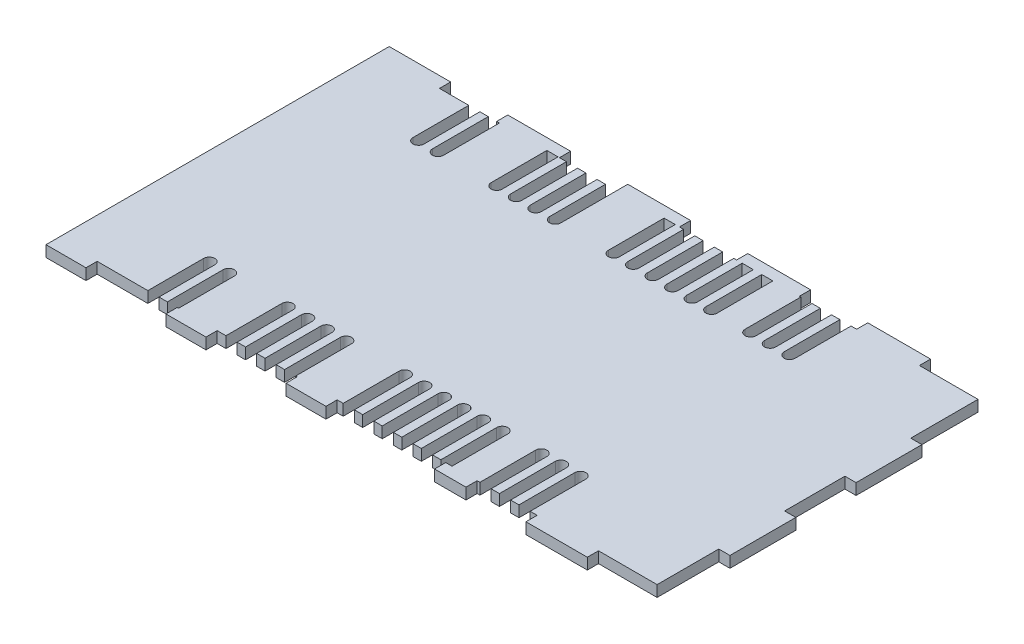
SolidWorks part; units mm, degrees
ref_plane "Front Plane" through (0, 0, 0) normal (0, 0, 1) x (1, 0, 0)
ref_plane "Top Plane" through (0, 0, 0) normal (0, 1, 0) x (1, 0, 0)
ref_plane "Right Plane" through (0, 0, 0) normal (1, 0, 0) x (0, 0, -1)
sketch "Sketch1" plane through (0, 0, 0) normal (0, 1, 0) x (1, 0, 0)
  line L1 (0, 0) -> (215, 0)
  line L2 (0, 0) -> (0, 115)
  line L3 (0, 115) -> (215, 115)
  line L4 (215, 0) -> (215, 115)
  dimension "D1" = 215
  dimension "D2" = 115
extrude "Boss-Extrude1" add sketch "Sketch1" along normal blind 4
sketch "Sketch2" plane through (0, 4, 0) normal (0, 1, 0) x (1, 0, 0)
  line L0 (43, -4) -> (43, 0)
  line L1 (0, -4) -> (21.5, -4)
  line L2 (0, -4) -> (0, 0)
  line L3 (0, 0) -> (21.5, 0)
  line L4 (21.5, -4) -> (21.5, 0)
  line L5 (43, -4) -> (64.5, -4)
  line L6 (64.5, -4) -> (64.5, 0)
  line L7 (43, 0) -> (64.5, 0)
  line L8 (86, -4) -> (86, 0)
  line L9 (86, -4) -> (107.5, -4)
  line L10 (107.5, -4) -> (107.5, 0)
  line L11 (86, 0) -> (107.5, 0)
  line L12 (129, -4) -> (129, 0)
  line L13 (129, -4) -> (150.5, -4)
  line L14 (150.5, -4) -> (150.5, 0)
  line L15 (129, 0) -> (150.5, 0)
  line L16 (172, -4) -> (172, 0)
  line L17 (172, -4) -> (193.5, -4)
  line L18 (193.5, -4) -> (193.5, 0) construction
  line L19 (172, 0) -> (193.5, 0)
  line L20 (193.5, -4) -> (194, -4)
  line L21 (194, -4) -> (194, 0)
  line L22 (0, 0) -> (215, 0) construction
  line L23 (194, 0) -> (193.5, 0)
  dimension "D1" = 4
  dimension "D2" = 21.5
  dimension "D3" = 5
extrude "Boss-Extrude2" add sketch "Sketch2" against normal blind 4
sketch "Sketch3" plane through (0, 4, 0) normal (0, 1, 0) x (1, 0, 0)
  line L0 (57.33, -4) -> (57.33, 0)
  line L1 (14.33, -4) -> (28.6633, -4)
  line L2 (14.33, -4) -> (14.33, 0)
  line L3 (14.33, 0) -> (28.6633, 0)
  line L4 (28.6633, -4) -> (28.6633, 0)
  line L5 (0, 115) -> (0, -4) construction
  line L6 (21.5, 0) -> (43, 0) construction
  line L7 (0, -4) -> (21.5, -4) construction
  line L8 (57.33, -4) -> (71.6633, -4)
  line L9 (71.6633, -4) -> (71.6633, 0)
  line L10 (57.33, 0) -> (71.6633, 0)
  line L11 (100.33, -4) -> (100.33, 0)
  line L12 (100.33, -4) -> (114.6633, -4)
  line L13 (114.6633, -4) -> (114.6633, 0)
  line L14 (100.33, 0) -> (114.6633, 0)
  dimension "D1" = 14.3333
  dimension "D2" = 14.33
  dimension "D3" = 3
extrude "Cut-Extrude1" cut sketch "Sketch3" against normal blind 4
sketch "Sketch4" plane through (0, 4, 0) normal (0, 1, 0) x (1, 0, 0)
  line L1 (129, -4) -> (139.25, -4)
  line L2 (129, -4) -> (129, 0)
  line L3 (129, 0) -> (139.25, 0)
  line L4 (139.25, -4) -> (139.25, 0)
  dimension "D1" = 10.25
extrude "Cut-Extrude2" cut sketch "Sketch4" against normal blind 10
sketch "Sketch5" plane through (0, 0, 0) normal (0, -1, 0) x (1, 0, 0)
  line L0 (215, 0) -> (215, -115) construction
  line L1 (215, -22.1) -> (219, -22.1)
  line L2 (215, -22.1) -> (215, -45.7)
  line L3 (215, -45.7) -> (219, -45.7)
  line L4 (219, -22.1) -> (219, -45.7)
  line L5 (194, 0) -> (215, 0) construction
  line L6 (215, -67.3) -> (215, -90.9)
  line L7 (215, -67.3) -> (219, -67.3)
  line L8 (219, -67.3) -> (219, -90.9)
  line L9 (215, -90.9) -> (219, -90.9)
  dimension "D3" = 4
  dimension "D1" = 23.6
  dimension "D2" = 22.1
  dimension "D4" = 2
extrude "Boss-Extrude3" add sketch "Sketch5" against normal blind 4
sketch "Sketch6" plane through (0, 0, 0) normal (0, -1, 0) x (1, 0, 0)
  line L0 (215, -115) -> (0, -115) construction
  line L1 (194, -115) -> (171.5, -115)
  line L2 (194, -115) -> (194, -119)
  line L3 (194, -119) -> (171.5, -119)
  line L4 (171.5, -115) -> (171.5, -119)
  line L5 (215, -90.9) -> (215, -115) construction
  line L6 (151, -115) -> (151, -119)
  line L7 (151, -115) -> (128.5, -115)
  line L8 (128.5, -115) -> (128.5, -119)
  line L9 (151, -119) -> (128.5, -119)
  line L10 (108, -115) -> (108, -119)
  line L11 (108, -115) -> (85.5, -115)
  line L12 (85.5, -115) -> (85.5, -119)
  line L13 (108, -119) -> (85.5, -119)
  line L14 (65, -115) -> (65, -119)
  line L15 (65, -115) -> (42.5, -115)
  line L16 (42.5, -115) -> (42.5, -119)
  line L17 (65, -119) -> (42.5, -119)
  line L18 (22, -115) -> (22, -119)
  line L19 (22, -115) -> (0, -115)
  line L21 (22, -119) -> (0, -119)
  line L22 (0, -115) -> (0, -119)
  line L24 (-0.5, -115) -> (-0.5, -119) [skipped]
  dimension "D1" = 22.5
  dimension "D2" = 21
  dimension "D3" = 4
  dimension "D4" = 5
extrude "Boss-Extrude4" add sketch "Sketch6" against normal blind 4
sketch "Sketch7" plane through (0, 0, 0) normal (0, -1, 0) x (-1, 0, 0)
  line L0 (-14.33, 0) -> (-43, 0) construction
  line L3 (-118.4996, 95) -> (-118.4996, 98) construction
  line L4 (0, 57.5) -> (-215, 57.5) construction
  line L11 (0, 119) -> (0, -4) construction
  line L14 (-215, 45.7) -> (-215, 67.3) construction
  line L17 (-120.4996, 0) -> (-116.4996, 0)
  line L22 (-32.4996, 95) -> (-32.4996, 115)
  line L23 (-36.4996, 115) -> (-32.4996, 115)
  line L26 (-127.4996, 20) -> (-127.4996, 0)
  line L27 (-118.4996, 20) -> (-118.4996, 17) construction
  line L28 (-36.4996, 95) -> (-36.4996, 115)
  line L29 (-116.4996, 20) -> (-116.4996, 0)
  line L30 (-120.4996, 20) -> (-120.4996, 0)
  line L31 (-127.4996, 0) -> (-123.4996, 0)
  line L32 (-123.4996, 20) -> (-123.4996, 0)
  line L33 (-134.4996, 20) -> (-134.4996, 0)
  line L34 (-134.4996, 0) -> (-130.4996, 0)
  line L35 (-130.4996, 20) -> (-130.4996, 0)
  line L36 (-141.4996, 20) -> (-141.4996, 0)
  line L37 (-141.4996, 0) -> (-137.4996, 0)
  line L38 (-137.4996, 20) -> (-137.4996, 0)
  line L39 (-148.4996, 20) -> (-148.4996, 0)
  line L40 (-148.4996, 0) -> (-144.4996, 0)
  line L41 (-144.4996, 20) -> (-144.4996, 0)
  line L42 (-155.4996, 20) -> (-155.4996, 0)
  line L43 (-155.4996, 0) -> (-151.4996, 0)
  line L44 (-151.4996, 20) -> (-151.4996, 0)
  line L45 (-162.4996, 20) -> (-162.4996, 0)
  line L46 (-162.4996, 0) -> (-158.4996, 0)
  line L47 (-158.4996, 20) -> (-158.4996, 0)
  line L48 (-169.4996, 20) -> (-169.4996, 0)
  line L49 (-169.4996, 0) -> (-165.4996, 0)
  line L50 (-165.4996, 20) -> (-165.4996, 0)
  line L51 (-176.4996, 20) -> (-176.4996, 0)
  line L52 (-176.4996, 0) -> (-172.4996, 0)
  line L53 (-172.4996, 20) -> (-172.4996, 0)
  line L54 (-113.4996, 20) -> (-113.4996, 0)
  line L55 (-113.4996, 0) -> (-109.4996, 0)
  line L56 (-109.4996, 20) -> (-109.4996, 0)
  line L57 (-106.4996, 20) -> (-106.4996, 0)
  line L58 (-106.4996, 0) -> (-102.4996, 0)
  line L59 (-102.4996, 20) -> (-102.4996, 0)
  line L60 (-99.4996, 20) -> (-99.4996, 0)
  line L61 (-99.4996, 0) -> (-95.4996, 0)
  line L62 (-95.4996, 20) -> (-95.4996, 0)
  line L63 (-92.4996, 20) -> (-92.4996, 0)
  line L64 (-92.4996, 0) -> (-88.4996, 0)
  line L65 (-88.4996, 20) -> (-88.4996, 0)
  line L66 (-85.4996, 20) -> (-85.4996, 0)
  line L67 (-85.4996, 0) -> (-81.4996, 0)
  line L68 (-81.4996, 20) -> (-81.4996, 0)
  line L69 (-78.4996, 20) -> (-78.4996, 0)
  line L70 (-78.4996, 0) -> (-74.4996, 0)
  line L71 (-74.4996, 20) -> (-74.4996, 0)
  line L72 (-71.4996, 20) -> (-71.4996, 0)
  line L73 (-71.4996, 0) -> (-67.4996, 0)
  line L74 (-67.4996, 20) -> (-67.4996, 0)
  line L75 (-64.4996, 20) -> (-64.4996, 0)
  line L76 (-64.4996, 0) -> (-60.4996, 0)
  line L77 (-60.4996, 20) -> (-60.4996, 0)
  line L78 (-57.4996, 20) -> (-57.4996, 0)
  line L79 (-57.4996, 0) -> (-53.4996, 0)
  line L80 (-53.4996, 20) -> (-53.4996, 0)
  line L81 (-50.4996, 20) -> (-50.4996, 0)
  line L82 (-50.4996, 0) -> (-46.4996, 0)
  line L83 (-46.4996, 20) -> (-46.4996, 0)
  line L84 (-43.4996, 20) -> (-43.4996, 0)
  line L85 (-43.4996, 0) -> (-39.4996, 0)
  line L86 (-39.4996, 20) -> (-39.4996, 0)
  line L87 (-183.4996, 20) -> (-183.4996, 0)
  line L88 (-183.4996, 0) -> (-179.4996, 0)
  line L89 (-179.4996, 20) -> (-179.4996, 0)
  line L90 (-36.4996, 20) -> (-36.4996, 0)
  line L91 (-36.4996, 0) -> (-32.4996, 0)
  line L92 (-32.4996, 20) -> (-32.4996, 0)
  line L93 (-179.4996, 95) -> (-179.4996, 115)
  line L94 (-183.4996, 115) -> (-179.4996, 115)
  line L95 (-183.4996, 95) -> (-183.4996, 115)
  line L96 (-39.4996, 95) -> (-39.4996, 115)
  line L97 (-43.4996, 115) -> (-39.4996, 115)
  line L98 (-43.4996, 95) -> (-43.4996, 115)
  line L99 (-46.4996, 95) -> (-46.4996, 115)
  line L100 (-50.4996, 115) -> (-46.4996, 115)
  line L101 (-50.4996, 95) -> (-50.4996, 115)
  line L102 (-53.4996, 95) -> (-53.4996, 115)
  line L103 (-57.4996, 115) -> (-53.4996, 115)
  line L104 (-57.4996, 95) -> (-57.4996, 115)
  line L105 (-60.4996, 95) -> (-60.4996, 115)
  line L106 (-64.4996, 115) -> (-60.4996, 115)
  line L107 (-64.4996, 95) -> (-64.4996, 115)
  line L108 (-67.4996, 95) -> (-67.4996, 115)
  line L109 (-71.4996, 115) -> (-67.4996, 115)
  line L110 (-71.4996, 95) -> (-71.4996, 115)
  line L111 (-74.4996, 95) -> (-74.4996, 115)
  line L112 (-78.4996, 115) -> (-74.4996, 115)
  line L113 (-78.4996, 95) -> (-78.4996, 115)
  line L114 (-81.4996, 95) -> (-81.4996, 115)
  line L115 (-85.4996, 115) -> (-81.4996, 115)
  line L116 (-85.4996, 95) -> (-85.4996, 115)
  line L117 (-88.4996, 95) -> (-88.4996, 115)
  line L118 (-92.4996, 115) -> (-88.4996, 115)
  line L119 (-92.4996, 95) -> (-92.4996, 115)
  line L120 (-95.4996, 95) -> (-95.4996, 115)
  line L121 (-99.4996, 115) -> (-95.4996, 115)
  line L122 (-99.4996, 95) -> (-99.4996, 115)
  line L123 (-102.4996, 95) -> (-102.4996, 115)
  line L124 (-106.4996, 115) -> (-102.4996, 115)
  line L125 (-106.4996, 95) -> (-106.4996, 115)
  line L126 (-109.4996, 95) -> (-109.4996, 115)
  line L127 (-113.4996, 115) -> (-109.4996, 115)
  line L128 (-113.4996, 95) -> (-113.4996, 115)
  line L129 (-172.4996, 95) -> (-172.4996, 115)
  line L130 (-176.4996, 115) -> (-172.4996, 115)
  line L131 (-176.4996, 95) -> (-176.4996, 115)
  line L132 (-165.4996, 95) -> (-165.4996, 115)
  line L133 (-169.4996, 115) -> (-165.4996, 115)
  line L134 (-169.4996, 95) -> (-169.4996, 115)
  line L135 (-158.4996, 95) -> (-158.4996, 115)
  line L136 (-162.4996, 115) -> (-158.4996, 115)
  line L137 (-162.4996, 95) -> (-162.4996, 115)
  line L138 (-151.4996, 95) -> (-151.4996, 115)
  line L139 (-155.4996, 115) -> (-151.4996, 115)
  line L140 (-155.4996, 95) -> (-155.4996, 115)
  line L141 (-144.4996, 95) -> (-144.4996, 115)
  line L142 (-148.4996, 115) -> (-144.4996, 115)
  line L143 (-148.4996, 95) -> (-148.4996, 115)
  line L144 (-137.4996, 95) -> (-137.4996, 115)
  line L145 (-141.4996, 115) -> (-137.4996, 115)
  line L146 (-141.4996, 95) -> (-141.4996, 115)
  line L147 (-130.4996, 95) -> (-130.4996, 115)
  line L148 (-134.4996, 115) -> (-130.4996, 115)
  line L149 (-134.4996, 95) -> (-134.4996, 115)
  line L150 (-123.4996, 95) -> (-123.4996, 115)
  line L151 (-127.4996, 115) -> (-123.4996, 115)
  line L152 (-120.4996, 95) -> (-120.4996, 115)
  line L153 (-116.4996, 95) -> (-116.4996, 115)
  line L154 (-127.4996, 95) -> (-127.4996, 115)
  line L155 (-120.4996, 115) -> (-116.4996, 115)
  arc A18 (-116.4996, 20) -> (-120.4996, 20) centre (-118.4996, 20) ccw
  arc A20 (-123.4996, 20) -> (-127.4996, 20) centre (-125.4996, 20) ccw
  arc A21 (-130.4996, 20) -> (-134.4996, 20) centre (-132.4996, 20) ccw
  arc A22 (-137.4996, 20) -> (-141.4996, 20) centre (-139.4996, 20) ccw
  arc A23 (-144.4996, 20) -> (-148.4996, 20) centre (-146.4996, 20) ccw
  arc A24 (-151.4996, 20) -> (-155.4996, 20) centre (-153.4996, 20) ccw
  arc A25 (-158.4996, 20) -> (-162.4996, 20) centre (-160.4996, 20) ccw
  arc A26 (-165.4996, 20) -> (-169.4996, 20) centre (-167.4996, 20) ccw
  arc A27 (-172.4996, 20) -> (-176.4996, 20) centre (-174.4996, 20) ccw
  arc A28 (-109.4996, 20) -> (-113.4996, 20) centre (-111.4996, 20) ccw
  arc A29 (-102.4996, 20) -> (-106.4996, 20) centre (-104.4996, 20) ccw
  arc A30 (-95.4996, 20) -> (-99.4996, 20) centre (-97.4996, 20) ccw
  arc A31 (-88.4996, 20) -> (-92.4996, 20) centre (-90.4996, 20) ccw
  arc A32 (-81.4996, 20) -> (-85.4996, 20) centre (-83.4996, 20) ccw
  arc A33 (-74.4996, 20) -> (-78.4996, 20) centre (-76.4996, 20) ccw
  arc A34 (-67.4996, 20) -> (-71.4996, 20) centre (-69.4996, 20) ccw
  arc A35 (-60.4996, 20) -> (-64.4996, 20) centre (-62.4996, 20) ccw
  arc A36 (-53.4996, 20) -> (-57.4996, 20) centre (-55.4996, 20) ccw
  arc A37 (-46.4996, 20) -> (-50.4996, 20) centre (-48.4996, 20) ccw
  arc A38 (-39.4996, 20) -> (-43.4996, 20) centre (-41.4996, 20) ccw
  arc A39 (-179.4996, 20) -> (-183.4996, 20) centre (-181.4996, 20) ccw
  arc A40 (-32.4996, 20) -> (-36.4996, 20) centre (-34.4996, 20) ccw
  arc A41 (-32.4996, 95) -> (-36.4996, 95) centre (-34.4996, 95) cw
  arc A42 (-179.4996, 95) -> (-183.4996, 95) centre (-181.4996, 95) cw
  arc A43 (-39.4996, 95) -> (-43.4996, 95) centre (-41.4996, 95) cw
  arc A44 (-46.4996, 95) -> (-50.4996, 95) centre (-48.4996, 95) cw
  arc A45 (-53.4996, 95) -> (-57.4996, 95) centre (-55.4996, 95) cw
  arc A46 (-60.4996, 95) -> (-64.4996, 95) centre (-62.4996, 95) cw
  arc A47 (-67.4996, 95) -> (-71.4996, 95) centre (-69.4996, 95) cw
  arc A48 (-74.4996, 95) -> (-78.4996, 95) centre (-76.4996, 95) cw
  arc A49 (-81.4996, 95) -> (-85.4996, 95) centre (-83.4996, 95) cw
  arc A50 (-88.4996, 95) -> (-92.4996, 95) centre (-90.4996, 95) cw
  arc A51 (-95.4996, 95) -> (-99.4996, 95) centre (-97.4996, 95) cw
  arc A52 (-102.4996, 95) -> (-106.4996, 95) centre (-104.4996, 95) cw
  arc A53 (-109.4996, 95) -> (-113.4996, 95) centre (-111.4996, 95) cw
  arc A54 (-172.4996, 95) -> (-176.4996, 95) centre (-174.4996, 95) cw
  arc A55 (-165.4996, 95) -> (-169.4996, 95) centre (-167.4996, 95) cw
  arc A56 (-158.4996, 95) -> (-162.4996, 95) centre (-160.4996, 95) cw
  arc A57 (-151.4996, 95) -> (-155.4996, 95) centre (-153.4996, 95) cw
  arc A58 (-144.4996, 95) -> (-148.4996, 95) centre (-146.4996, 95) cw
  arc A59 (-137.4996, 95) -> (-141.4996, 95) centre (-139.4996, 95) cw
  arc A60 (-130.4996, 95) -> (-134.4996, 95) centre (-132.4996, 95) cw
  arc A61 (-123.4996, 95) -> (-127.4996, 95) centre (-125.4996, 95) cw
  arc A62 (-116.4996, 95) -> (-120.4996, 95) centre (-118.4996, 95) cw
  point P1 (-34.4996, 0)
  point P14 (-118.4996, 28.0614)
  dimension "D2" = 2
  dimension "D3" = 2
  dimension "D4" = 20
  dimension "D13" = 9
  dimension "D14" = 12
extrude "Cut-Extrude3" cut sketch "Sketch7" against normal blind 4
sketch "Sketch8" plane through (0, 0, 0) normal (0, -1, 0) x (1, 0, 0)
  line L0 (46.4996, 0) -> (46.4996, -20) construction
  line L5 (50.4996, 0) -> (46.4996, 0) construction
  line L6 (50.4996, -20) -> (50.4996, 0) construction
  line L7 (46.4996, 0) -> (46.4996, -20)
  line L8 (50.4996, 0) -> (46.4996, 0)
  line L9 (50.4996, -20) -> (50.4996, 0)
  line L10 (57.33, 0) -> (53.4996, 0) construction
  line L11 (57.4996, -20) -> (57.4996, 0) construction
  line L12 (53.4996, 0) -> (53.4996, -20) construction
  line L13 (57.33, 0) -> (53.4996, 0)
  line L14 (57.4996, -20) -> (57.4996, 0)
  line L15 (53.4996, 0) -> (53.4996, -20)
  line L16 (57.33, 0) -> (57.4996, 0)
  line L17 (99.4996, -20) -> (99.4996, 0) construction
  line L18 (95.4996, 0) -> (95.4996, -20) construction
  line L19 (99.4996, 0) -> (95.4996, 0) construction
  line L20 (92.4996, 0) -> (88.4996, 0) construction
  line L21 (88.4996, 0) -> (88.4996, -20) construction
  line L22 (92.4996, -20) -> (92.4996, 0) construction
  line L23 (99.4996, -20) -> (99.4996, 0)
  line L24 (95.4996, 0) -> (95.4996, -20)
  line L25 (99.4996, 0) -> (95.4996, 0)
  line L26 (92.4996, 0) -> (88.4996, 0)
  line L27 (88.4996, 0) -> (88.4996, -20)
  line L28 (92.4996, -20) -> (92.4996, 0)
  line L29 (148.4996, -20) -> (148.4996, 0) construction
  line L30 (148.4996, 0) -> (144.4996, 0) construction
  line L31 (144.4996, 0) -> (144.4996, -20) construction
  line L32 (148.4996, -20) -> (148.4996, 0)
  line L33 (148.4996, 0) -> (144.4996, 0)
  line L34 (144.4996, 0) -> (144.4996, -20)
  line L35 (183.4996, 0) -> (179.4996, 0) construction
  line L36 (183.4996, -20) -> (183.4996, 0) construction
  line L37 (179.4996, 0) -> (179.4996, -20) construction
  line L38 (176.4996, -20) -> (176.4996, 0) construction
  line L39 (176.4996, 0) -> (172.4996, 0) construction
  line L40 (172.4996, 0) -> (172.4996, -20) construction
  line L41 (183.4996, 0) -> (179.4996, 0)
  line L42 (183.4996, -20) -> (183.4996, 0)
  line L43 (179.4996, 0) -> (179.4996, -20)
  line L44 (176.4996, -20) -> (176.4996, 0)
  line L45 (176.4996, 0) -> (172.4996, 0)
  line L46 (172.4996, 0) -> (172.4996, -20)
  line L47 (0, -57.5) -> (215, -57.5) construction
  line L48 (0, -119) -> (0, 4) construction
  line L49 (215, -45.7) -> (215, -67.3) construction
  line L50 (172.4996, -115) -> (172.4996, -95)
  line L51 (176.4996, -115) -> (172.4996, -115)
  line L52 (176.4996, -95) -> (176.4996, -115)
  line L53 (179.4996, -115) -> (179.4996, -95)
  line L54 (183.4996, -95) -> (183.4996, -115)
  line L55 (183.4996, -115) -> (179.4996, -115)
  line L56 (144.4996, -115) -> (144.4996, -95)
  line L57 (148.4996, -115) -> (144.4996, -115)
  line L58 (148.4996, -95) -> (148.4996, -115)
  line L59 (92.4996, -95) -> (92.4996, -115)
  line L60 (88.4996, -115) -> (88.4996, -95)
  line L61 (92.4996, -115) -> (88.4996, -115)
  line L62 (99.4996, -115) -> (95.4996, -115)
  line L63 (95.4996, -115) -> (95.4996, -95)
  line L64 (99.4996, -95) -> (99.4996, -115)
  line L65 (57.33, -115) -> (57.4996, -115)
  line L66 (53.4996, -115) -> (53.4996, -95)
  line L67 (57.4996, -95) -> (57.4996, -115)
  line L68 (57.33, -115) -> (53.4996, -115)
  line L69 (50.4996, -95) -> (50.4996, -115)
  line L70 (50.4996, -115) -> (46.4996, -115)
  line L71 (46.4996, -115) -> (46.4996, -95)
  arc A0 (46.4996, -20) -> (50.4996, -20) centre (48.4996, -20) ccw construction
  arc A1 (46.4996, -20) -> (50.4996, -20) centre (48.4996, -20) ccw
  arc A2 (53.4996, -20) -> (57.4996, -20) centre (55.4996, -20) ccw construction
  arc A3 (53.4996, -20) -> (57.4996, -20) centre (55.4996, -20) ccw
  arc A4 (95.4996, -20) -> (99.4996, -20) centre (97.4996, -20) ccw construction
  arc A5 (88.4996, -20) -> (92.4996, -20) centre (90.4996, -20) ccw construction
  arc A6 (95.4996, -20) -> (99.4996, -20) centre (97.4996, -20) ccw
  arc A7 (88.4996, -20) -> (92.4996, -20) centre (90.4996, -20) ccw
  arc A8 (144.4996, -20) -> (148.4996, -20) centre (146.4996, -20) ccw construction
  arc A9 (144.4996, -20) -> (148.4996, -20) centre (146.4996, -20) ccw
  arc A10 (179.4996, -20) -> (183.4996, -20) centre (181.4996, -20) ccw construction
  arc A11 (172.4996, -20) -> (176.4996, -20) centre (174.4996, -20) ccw construction
  arc A12 (179.4996, -20) -> (183.4996, -20) centre (181.4996, -20) ccw
  arc A13 (172.4996, -20) -> (176.4996, -20) centre (174.4996, -20) ccw
  arc A14 (172.4996, -95) -> (176.4996, -95) centre (174.4996, -95) cw
  arc A15 (179.4996, -95) -> (183.4996, -95) centre (181.4996, -95) cw
  arc A16 (144.4996, -95) -> (148.4996, -95) centre (146.4996, -95) cw
  arc A17 (88.4996, -95) -> (92.4996, -95) centre (90.4996, -95) cw
  arc A18 (95.4996, -95) -> (99.4996, -95) centre (97.4996, -95) cw
  arc A19 (53.4996, -95) -> (57.4996, -95) centre (55.4996, -95) cw
  arc A20 (46.4996, -95) -> (50.4996, -95) centre (48.4996, -95) cw
extrude "Boss-Extrude5" add sketch "Sketch8" against normal blind 4
equation "\"Dikte\"= 4"
equation "\"D1@Sketch1\"=225-10"
equation "\"Tolerantie\"= 0.5"
equation "\"D2@Sketch6\"=21.5-\"Tolerantie\""
equation "\"D1@Sketch6\"=21.5+2*\"Tolerantie\""
equation "\"D2@Sketch5\"=22.6-\"Tolerantie\""
equation "\"D1@Sketch5\"=22.60mm+2*\"Tolerantie\""
equation "\"D4@Sketch2\"=\"Tolerantie\""
equation "\"D1@Sketch4\"=10.75-\"Tolerantie\""
